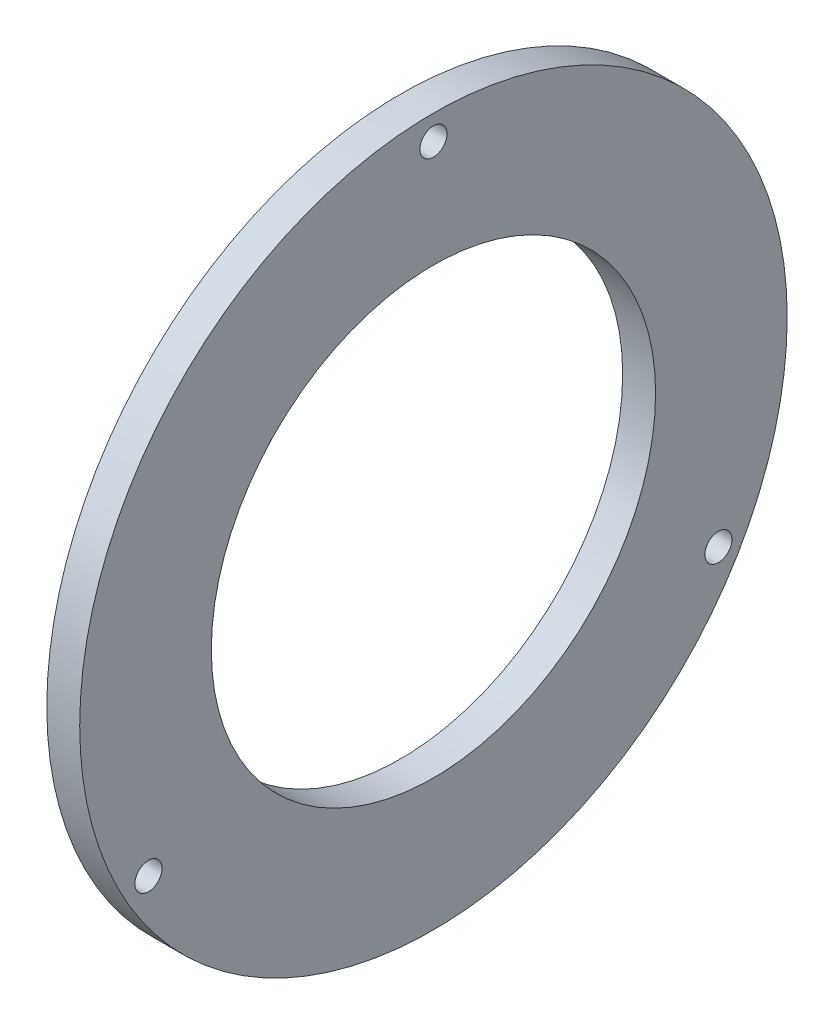
SolidWorks part; units mm, degrees
ref_plane "Front Plane" through (0, 0, 0) normal (0, 0, 1) x (1, 0, 0)
ref_plane "Top Plane" through (0, 0, 0) normal (0, 1, 0) x (1, 0, 0)
ref_plane "Right Plane" through (0, 0, 0) normal (1, 0, 0) x (0, 0, -1)
sketch "Axial profile (mm)" plane through (0, 0, 0) normal (0, 0, 1) x (1, 0, 0)
  line L0 (-110, 0) -> (75, 0) construction
  line L1 (131.7, 27) -> (135.7, 27)
  line L2 (135.7, 27) -> (135.7, 43)
  line L3 (135.7, 43) -> (131.7, 43)
  line L4 (131.7, 43) -> (131.7, 27)
revolve "Full revolution" add sketch "Axial profile (mm)" angle 360 about L0
sketch "Sketch2" plane through (0, 0, 0) normal (1, 0, 0) x (0, 0, -1)
  circle A0 centre (0, 40) radius 1.65
  circle A1 centre (-34.641, -20) radius 1.65
  circle A2 centre (34.641, -20) radius 1.65
extrude "Axial holes" cut sketch "Sketch2" against normal through all and the other way through all
